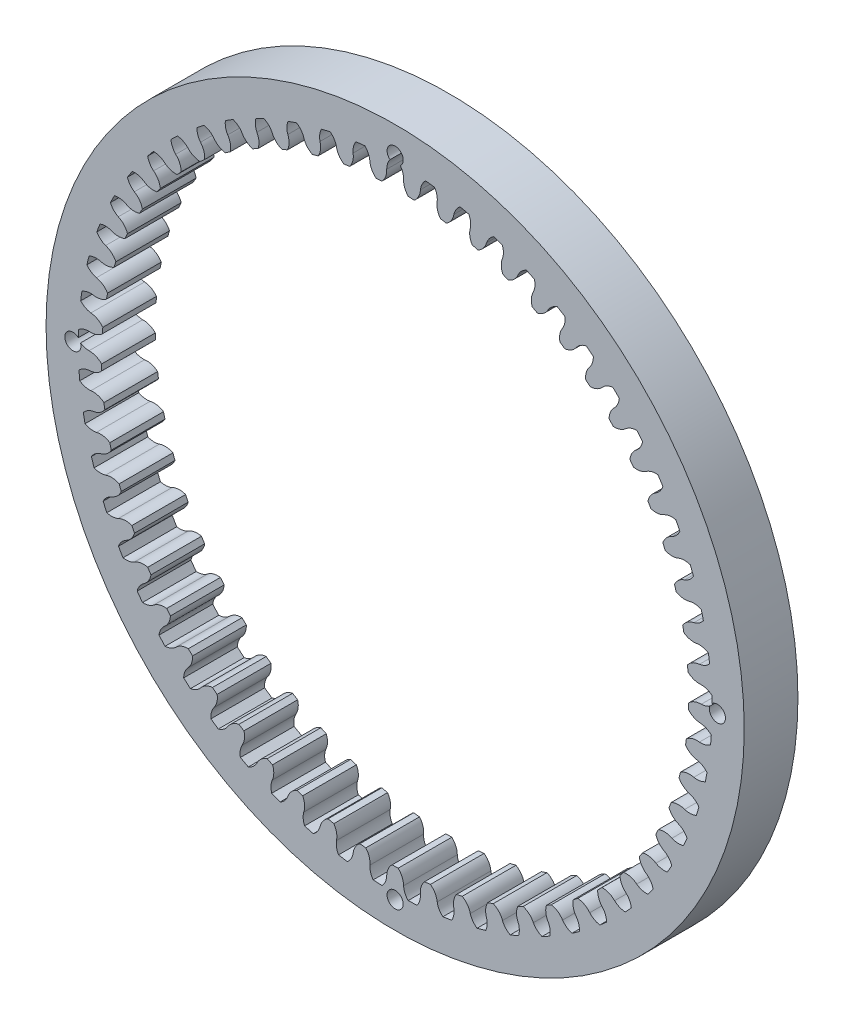
SolidWorks part; units mm, degrees
ref_plane "Alzado" through (0, 0, 0) normal (0, 0, 1) x (1, 0, 0)
ref_plane "Planta" through (0, 0, 0) normal (0, 1, 0) x (1, 0, 0)
ref_plane "Vista lateral" through (0, 0, 0) normal (1, 0, 0) x (0, 0, -1)
sketch "Croquis1" plane through (0, 0, 0) normal (0, 0, 1) x (1, 0, 0)
  circle A0 centre (0, 0) radius 65
  circle A1 centre (0, 0) radius 54.665
  dimension "D1" = 130
  dimension "D2" = 109.33
extrude "Saliente-Extruir1" add sketch "Croquis1" along normal blind 10
sketch "Croquis2" plane through (0, 0, 10) normal (0, 0, 1) x (1, 0, 0)
  arc A0 (2.4607, 54.6096) -> (-2.4607, 54.6096) centre (0, 0) ccw
  arc A3 (-2.4607, 54.6096) -> (-1.57, 56.9784) centre (-4.7052, 56.8055) ccw
  arc A5 (-0.8376, 58.9941) -> (-1.57, 56.9784) centre (1.57, 56.9784) ccw
  arc A6 (1.57, 56.9784) -> (2.4607, 54.6096) centre (4.7052, 56.8055) ccw
  arc A7 (0.8376, 58.9941) -> (-0.8376, 58.9941) centre (0, 0) ccw
  arc A9 (1.57, 56.9784) -> (0.8376, 58.9941) centre (-1.57, 56.9784) ccw
  dimension "D3" = 6.28
extrude "Cortar-Extruir1" cut sketch "Croquis2" against normal through all
pattern_circular "MatrizC1" count 57 over 360 about axis through (0, 0, 0) along (0, 0, 1) of "Cortar-Extruir1"
sketch "Croquis3" plane through (0, 0, 10) normal (0, 0, 1) x (1, 0, 0)
  line L0 (0.002, 59.9997) -> (0.002, 0) construction
  line L1 (0.002, 0) -> (65, 0) construction
  circle A1 centre (0.002, 59.9997) radius 1.5
  circle A2 centre (0, 0) radius 65 construction
  circle A4 centre (60.0007, -0.001) radius 1.5
  circle A6 centre (0, -59.9997) radius 1.5
  circle A7 centre (0, 0) radius 65 construction
  circle A8 centre (-59.9987, 0.001) radius 1.5
  point P26 (0.001, 0)
  dimension "D1" = 3
  dimension "D2" = 90
  dimension "D3" = 4
extrude "Cortar-Extruir2" cut sketch "Croquis3" against normal through all
